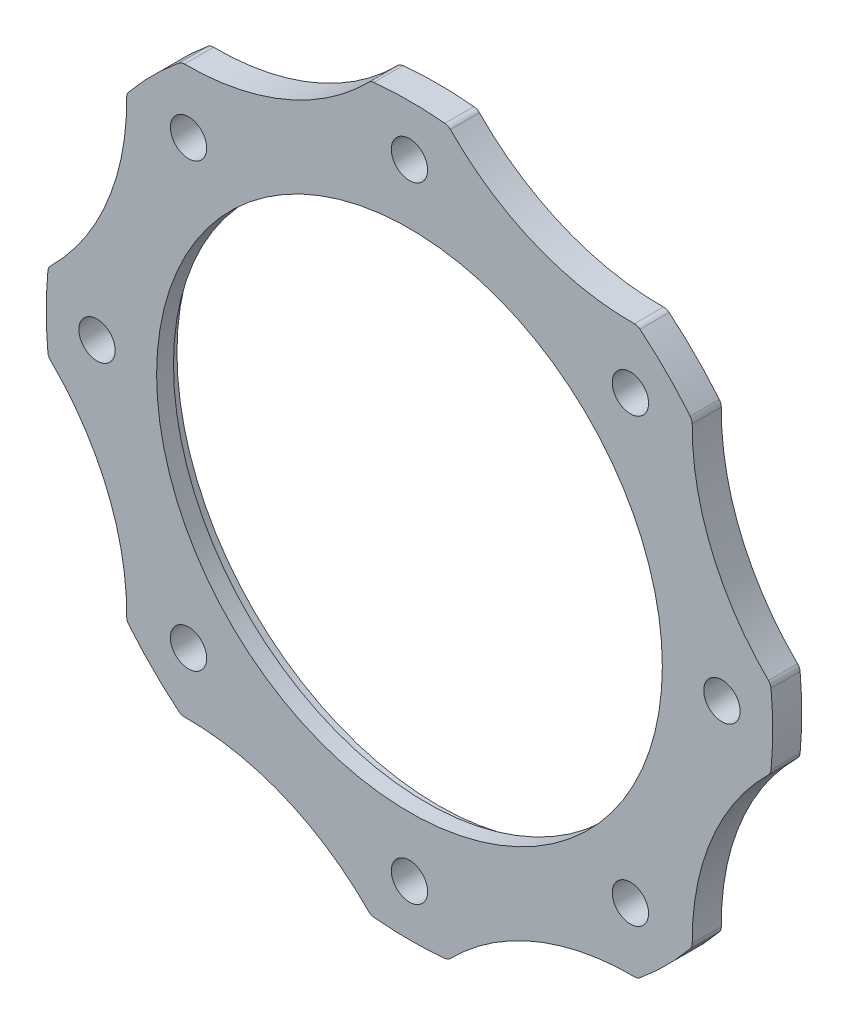
SolidWorks part; units mm, degrees
material "AISI 304"
ref_plane "Спереди" through (0, 0, 0) normal (0, 0, 1) x (1, 0, 0)
ref_plane "Сверху" through (0, 0, 0) normal (0, 1, 0) x (1, 0, 0)
ref_plane "Справа" through (0, 0, 0) normal (1, 0, 0) x (0, 0, -1)
other "Configuration Table"
sketch "Эскиз1" plane through (0, 0, 0) normal (0, 0, 1) x (1, 0, 0)
  line L0 (0, 107.5) -> (0, 0) construction
  circle A0 centre (0, 0) radius 87
  circle A2 centre (76.014, 76.014) radius 6.25
  circle A3 centre (0, 0) radius 125
  circle A4 centre (107.5, 0) radius 6.25
  circle A5 centre (76.014, -76.014) radius 6.25
  circle A6 centre (0, -107.5) radius 6.25
  circle A7 centre (-76.014, -76.014) radius 6.25
  circle A8 centre (-107.5, 0) radius 6.25
  circle A9 centre (-76.014, 76.014) radius 6.25
  circle A10 centre (0, 107.5) radius 6.25
  circle A11 centre (0, 0) radius 107.5 construction
  point P24 (0, 0)
  dimension "D2" = 174
  dimension "D3" = 250
  dimension "D4" = 215
  dimension "D5" = 12.5
  dimension "D1" = 8
extrude "Бобышка-Вытянуть1" add sketch "Эскиз1" along normal blind 10
sketch "Эскиз3" plane through (0, 0, 10) normal (0, 0, 1) x (1, 0, 0)
  arc A12 (-12.2088, 124.4024) -> (-14.0579, 123.517) centre (-11.9158, 121.4167) ccw
  arc A13 (-12.2088, 124.4024) -> (-79.3328, 96.5987) centre (0, 0) ccw
  arc A14 (-77.3993, 97.2802) -> (-79.3328, 96.5987) centre (-77.4288, 94.2803) ccw
  arc A15 (-77.3993, 97.2802) -> (-14.0579, 123.517) centre (-76.5367, 184.7759) ccw
extrude "Вырез-Вытянуть3" cut sketch "Эскиз3" against normal through all both and the other way through all
pattern_circular "Круговой массив1" count 8 over 360 of "Вырез-Вытянуть3"
sketch "Эскиз4" plane through (0, 0, 0) normal (0, 0, -1) x (-1, 0, 0)
  circle A0 centre (0, 0) radius 90
  dimension "D1" = 180
extrude "Вырез-Вытянуть4" cut sketch "Эскиз4" against normal blind 4.2
